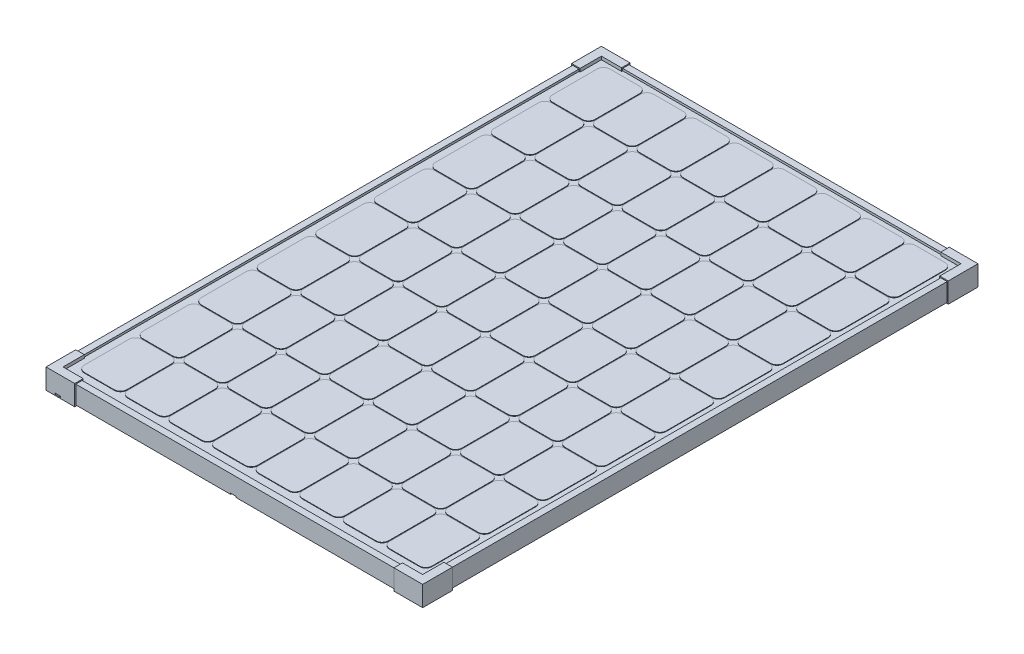
SolidWorks part; units mm, degrees
material "Aleación 1060"
ref_plane "Plan de face" through (0, 0, 0) normal (0, 0, 1) x (1, 0, 0)
ref_plane "Plan de dessus" through (0, 0, 0) normal (0, 1, 0) x (1, 0, 0)
ref_plane "Plan de droite" through (0, 0, 0) normal (1, 0, 0) x (0, 0, -1)
sketch "Croquis1" plane through (0, 0, 0) normal (0, 1, 0) x (1, 0, 0)
  line L1 (0, 0) -> (352, 0)
  line L2 (0, 0) -> (0, 520)
  line L3 (0, 520) -> (352, 520)
  line L4 (352, 0) -> (352, 520)
  dimension "D1" = 520
  dimension "D2" = 352
extrude "Saliente-Extruir1" add sketch "Croquis1" along normal blind 17
sketch "Croquis3" plane through (0, 17, 0) normal (0, 1, 0) x (1, 0, 0)
  line L0 (346, 6) -> (346, 514)
  line L1 (346, 514) -> (6, 514)
  line L2 (6, 514) -> (6, 6)
  line L3 (6, 6) -> (346, 6)
  line L5 (352, 520) -> (0, 520) construction
  line L6 (0, 0) -> (352, 0) construction
  line L7 (0, 520) -> (0, 0) construction
  line L8 (352, 0) -> (352, 520) construction
  dimension "D1" = 6
  dimension "D2" = 6
  dimension "D3" = 6
  dimension "D4" = 6
extrude "Cortar-Extruir1" cut sketch "Croquis3" against normal blind 2
shell "Vaciado1" thickness 1
sketch "Croquis2" plane through (0, 0, 0) normal (0, -1, 0) x (1, 0, 0)
  line L0 (17, -17) -> (17, -503)
  line L1 (17, -503) -> (335, -503)
  line L2 (335, -503) -> (335, -17)
  line L3 (335, -17) -> (17, -17)
  line L4 (0, 0) -> (0, -520)
  line L5 (0, -520) -> (352, -520)
  line L6 (352, -520) -> (352, 0)
  line L7 (352, 0) -> (0, 0)
  line L8 (0, 0) -> (0, -520)
  line L9 (0, -520) -> (352, -520)
  line L10 (352, -520) -> (352, 0)
  line L11 (352, 0) -> (0, 0)
  dimension "D1" = 0
  dimension "D2" = 17
extrude "Saliente-Extruir2" add sketch "Croquis2" against normal blind 1
sketch "Croquis4" plane through (0, 17, 0) normal (0, 1, 0) x (1, 0, 0)
  line L1 (0, 520) -> (0, 0) construction
  line L2 (6, 514) -> (6, 6) construction
  line L3 (352, 520) -> (0, 520) construction
  line L4 (346, 514) -> (6, 514) construction
  line L8 (26, 521) -> (-1, 521)
  line L9 (-1, 521) -> (-1, 493)
  line L10 (26, 513) -> (7, 513)
  line L11 (7, 513) -> (7, 493)
  line L12 (26, 521) -> (26, 513)
  line L13 (-1, 493) -> (7, 493)
  point P16 (3, 493)
  dimension "D3" = 27
  dimension "D4" = 28
  dimension "D1" = 1
  dimension "D2" = 1
  dimension "D5" = 1
  dimension "D6" = 1
extrude "Saliente-Extruir3" add sketch "Croquis4" along normal blind 1 and the other way blind 17
sketch "Croquis5" plane through (0, 0, 0) normal (0, -1, 0) x (1, 0, 0)
  line L2 (-1, -521) -> (-1, -493)
  line L3 (26, -521) -> (-1, -521)
  line L4 (-1, -493) -> (18, -493)
  line L5 (18, -493) -> (18, -502)
  line L6 (18, -502) -> (26, -502)
  line L7 (26, -502) -> (26, -521)
  line L9 (17, -17) -> (17, -503) construction
  line L10 (0, -493) -> (0, 0) construction
  dimension "D1" = 19
  dimension "D2" = 9
  dimension "D3" = 27
  dimension "D4" = 1
  dimension "D5" = 1
  dimension "D6" = 19
  dimension "D7" = 8
  dimension "D8" = 28
  dimension "D9" = 521
extrude "Saliente-Extruir4" add sketch "Croquis5" along normal blind 1 and the other way blind 1
ref_plane "Plano1" through (0, 0, -260) normal (0, 0, 1) x (1, 0, 0)
mirror "Simetría1" about plane through (0, 0, -260) normal (0, 0, 1) of "Saliente-Extruir3", "Saliente-Extruir4"
ref_plane "Plano2" through (176, 0, 0) normal (-1, 0, 0) x (0, 0, 1)
mirror "Simetría2" about plane through (176, 0, 0) normal (-1, 0, 0) of "Simetría1", "Saliente-Extruir3", "Saliente-Extruir4"
sketch "Croquis6" plane through (0, 0, 0) normal (0, -1, 0) x (1, 0, 0)
  line L0 (10, -646.4035) -> (10, 241.4035) construction
  line L1 (7.5, -646.4035) -> (7.5, 241.4035)
  line L2 (12.5, -646.4035) -> (12.5, 241.4035)
  line L4 (0, -493) -> (0, -27) construction
  line L5 (17, -27) -> (17, -493) construction
  arc A0 (7.5, -646.4035) -> (12.5, -646.4035) centre (10, -646.4035) ccw
  arc A1 (12.5, 241.4035) -> (7.5, 241.4035) centre (10, 241.4035) ccw
  point P2 (10, -202.5)
  point P11 (17, -260)
  dimension "D1" = 10
  dimension "D2" = 57.5
extrude "Cortar-Extruir2" cut sketch "Croquis6" against normal blind 1
pattern_linear "MatrizL1" count 2 spacing 164 along (1, 0, 0) count 2 spacing 115 along (0, 0, -1) of "Cortar-Extruir2"
sketch "Croquis7" plane through (0, 14, 0) normal (0, -1, 0) x (1, 0, 0)
  line L0 (326, -17) -> (176.5, -17) construction
  line L1 (234.5, -93) -> (284.5, -93)
  line L2 (234.5, -93) -> (234.5, -26)
  line L3 (234.5, -26) -> (284.5, -26)
  line L4 (284.5, -93) -> (284.5, -26)
  line L5 (234.5, -93) -> (284.5, -26) construction
  line L6 (234.5, -26) -> (284.5, -93) construction
  line L7 (352, -27) -> (352, -493) construction
  point P0 (259.5, -59.5)
  dimension "D1" = 67
  dimension "D2" = 50
  dimension "D3" = 9
  dimension "D4" = 92.5
extrude "Saliente-Extruir5" add sketch "Croquis7" along normal blind 14
fillet "Redondeo1" radius 3 4 edges at (284.5, 7, -26) (234.5, 7, -26) (234.5, 7, -93) (284.5, 7, -93)
sketch "Croquis8" plane through (0, 15, 0) normal (0, 1, 0) x (1, 0, 0)
  line L0 (326, 514) -> (26, 514) construction
  line L1 (19, 509) -> (47, 509)
  line L2 (13, 503) -> (13, 461)
  line L3 (19, 455) -> (47, 455)
  line L4 (53, 503) -> (53, 461)
  line L5 (6, 493) -> (6, 27) construction
  line L6 (60, 509) -> (88, 509)
  line L7 (54, 503) -> (54, 461)
  line L8 (60, 455) -> (88, 455)
  line L9 (94, 503) -> (94, 461)
  line L10 (101, 509) -> (129, 509)
  line L11 (95, 503) -> (95, 461)
  line L12 (101, 455) -> (129, 455)
  line L13 (135, 503) -> (135, 461)
  line L14 (142, 509) -> (170, 509)
  line L15 (136, 503) -> (136, 461)
  line L16 (142, 455) -> (170, 455)
  line L17 (176, 503) -> (176, 461)
  line L18 (183, 509) -> (211, 509)
  line L19 (177, 503) -> (177, 461)
  line L20 (183, 455) -> (211, 455)
  line L21 (217, 503) -> (217, 461)
  line L22 (224, 509) -> (252, 509)
  line L23 (218, 503) -> (218, 461)
  line L24 (224, 455) -> (252, 455)
  line L25 (258, 503) -> (258, 461)
  line L26 (265, 509) -> (293, 509)
  line L27 (259, 503) -> (259, 461)
  line L28 (265, 455) -> (293, 455)
  line L29 (299, 503) -> (299, 461)
  line L30 (306, 509) -> (334, 509)
  line L31 (300, 503) -> (300, 461)
  line L32 (306, 455) -> (334, 455)
  line L33 (340, 503) -> (340, 461)
  line L34 (60, 454) -> (88, 454)
  line L35 (54, 448) -> (54, 406)
  line L36 (60, 400) -> (88, 400)
  line L37 (94, 448) -> (94, 406)
  line L38 (101, 454) -> (129, 454)
  line L39 (95, 448) -> (95, 406)
  line L40 (101, 400) -> (129, 400)
  line L41 (135, 448) -> (135, 406)
  line L42 (142, 454) -> (170, 454)
  line L43 (136, 448) -> (136, 406)
  line L44 (142, 400) -> (170, 400)
  line L45 (176, 448) -> (176, 406)
  line L46 (183, 454) -> (211, 454)
  line L47 (177, 448) -> (177, 406)
  line L48 (183, 400) -> (211, 400)
  line L49 (217, 448) -> (217, 406)
  line L50 (224, 454) -> (252, 454)
  line L51 (218, 448) -> (218, 406)
  line L52 (224, 400) -> (252, 400)
  line L53 (258, 448) -> (258, 406)
  line L54 (265, 454) -> (293, 454)
  line L55 (259, 448) -> (259, 406)
  line L56 (265, 400) -> (293, 400)
  line L57 (299, 448) -> (299, 406)
  line L58 (306, 454) -> (334, 454)
  line L59 (300, 448) -> (300, 406)
  line L60 (306, 400) -> (334, 400)
  line L61 (340, 448) -> (340, 406)
  line L62 (60, 399) -> (88, 399)
  line L63 (54, 393) -> (54, 351)
  line L64 (60, 345) -> (88, 345)
  line L65 (94, 393) -> (94, 351)
  line L66 (101, 399) -> (129, 399)
  line L67 (95, 393) -> (95, 351)
  line L68 (101, 345) -> (129, 345)
  line L69 (135, 393) -> (135, 351)
  line L70 (142, 399) -> (170, 399)
  line L71 (136, 393) -> (136, 351)
  line L72 (142, 345) -> (170, 345)
  line L73 (176, 393) -> (176, 351)
  line L74 (183, 399) -> (211, 399)
  line L75 (177, 393) -> (177, 351)
  line L76 (183, 345) -> (211, 345)
  line L77 (217, 393) -> (217, 351)
  line L78 (224, 399) -> (252, 399)
  line L79 (218, 393) -> (218, 351)
  line L80 (224, 345) -> (252, 345)
  line L81 (258, 393) -> (258, 351)
  line L82 (265, 399) -> (293, 399)
  line L83 (259, 393) -> (259, 351)
  line L84 (265, 345) -> (293, 345)
  line L85 (299, 393) -> (299, 351)
  line L86 (306, 399) -> (334, 399)
  line L87 (300, 393) -> (300, 351)
  line L88 (306, 345) -> (334, 345)
  line L89 (340, 393) -> (340, 351)
  line L90 (60, 344) -> (88, 344)
  line L91 (54, 338) -> (54, 296)
  line L92 (60, 290) -> (88, 290)
  line L93 (94, 338) -> (94, 296)
  line L94 (101, 344) -> (129, 344)
  line L95 (95, 338) -> (95, 296)
  line L96 (101, 290) -> (129, 290)
  line L97 (135, 338) -> (135, 296)
  line L98 (142, 344) -> (170, 344)
  line L99 (136, 338) -> (136, 296)
  line L100 (142, 290) -> (170, 290)
  line L101 (176, 338) -> (176, 296)
  line L102 (183, 344) -> (211, 344)
  line L103 (177, 338) -> (177, 296)
  line L104 (183, 290) -> (211, 290)
  line L105 (217, 338) -> (217, 296)
  line L106 (224, 344) -> (252, 344)
  line L107 (218, 338) -> (218, 296)
  line L108 (224, 290) -> (252, 290)
  line L109 (258, 338) -> (258, 296)
  line L110 (265, 344) -> (293, 344)
  line L111 (259, 338) -> (259, 296)
  line L112 (265, 290) -> (293, 290)
  line L113 (299, 338) -> (299, 296)
  line L114 (306, 344) -> (334, 344)
  line L115 (300, 338) -> (300, 296)
  line L116 (306, 290) -> (334, 290)
  line L117 (340, 338) -> (340, 296)
  line L118 (60, 289) -> (88, 289)
  line L119 (54, 283) -> (54, 241)
  line L120 (60, 235) -> (88, 235)
  line L121 (94, 283) -> (94, 241)
  line L122 (101, 289) -> (129, 289)
  line L123 (95, 283) -> (95, 241)
  line L124 (101, 235) -> (129, 235)
  line L125 (135, 283) -> (135, 241)
  line L126 (142, 289) -> (170, 289)
  line L127 (136, 283) -> (136, 241)
  line L128 (142, 235) -> (170, 235)
  line L129 (176, 283) -> (176, 241)
  line L130 (183, 289) -> (211, 289)
  line L131 (177, 283) -> (177, 241)
  line L132 (183, 235) -> (211, 235)
  line L133 (217, 283) -> (217, 241)
  line L134 (224, 289) -> (252, 289)
  line L135 (218, 283) -> (218, 241)
  line L136 (224, 235) -> (252, 235)
  line L137 (258, 283) -> (258, 241)
  line L138 (265, 289) -> (293, 289)
  line L139 (259, 283) -> (259, 241)
  line L140 (265, 235) -> (293, 235)
  line L141 (299, 283) -> (299, 241)
  line L142 (306, 289) -> (334, 289)
  line L143 (300, 283) -> (300, 241)
  line L144 (306, 235) -> (334, 235)
  line L145 (340, 283) -> (340, 241)
  line L146 (60, 234) -> (88, 234)
  line L147 (54, 228) -> (54, 186)
  line L148 (60, 180) -> (88, 180)
  line L149 (94, 228) -> (94, 186)
  line L150 (101, 234) -> (129, 234)
  line L151 (95, 228) -> (95, 186)
  line L152 (101, 180) -> (129, 180)
  line L153 (135, 228) -> (135, 186)
  line L154 (142, 234) -> (170, 234)
  line L155 (136, 228) -> (136, 186)
  line L156 (142, 180) -> (170, 180)
  line L157 (176, 228) -> (176, 186)
  line L158 (183, 234) -> (211, 234)
  line L159 (177, 228) -> (177, 186)
  line L160 (183, 180) -> (211, 180)
  line L161 (217, 228) -> (217, 186)
  line L162 (224, 234) -> (252, 234)
  line L163 (218, 228) -> (218, 186)
  line L164 (224, 180) -> (252, 180)
  line L165 (258, 228) -> (258, 186)
  line L166 (265, 234) -> (293, 234)
  line L167 (259, 228) -> (259, 186)
  line L168 (265, 180) -> (293, 180)
  line L169 (299, 228) -> (299, 186)
  line L170 (306, 234) -> (334, 234)
  line L171 (300, 228) -> (300, 186)
  line L172 (306, 180) -> (334, 180)
  line L173 (340, 228) -> (340, 186)
  line L174 (60, 179) -> (88, 179)
  line L175 (54, 173) -> (54, 131)
  line L176 (60, 125) -> (88, 125)
  line L177 (94, 173) -> (94, 131)
  line L178 (101, 179) -> (129, 179)
  line L179 (95, 173) -> (95, 131)
  line L180 (101, 125) -> (129, 125)
  line L181 (135, 173) -> (135, 131)
  line L182 (142, 179) -> (170, 179)
  line L183 (136, 173) -> (136, 131)
  line L184 (142, 125) -> (170, 125)
  line L185 (176, 173) -> (176, 131)
  line L186 (183, 179) -> (211, 179)
  line L187 (177, 173) -> (177, 131)
  line L188 (183, 125) -> (211, 125)
  line L189 (217, 173) -> (217, 131)
  line L190 (224, 179) -> (252, 179)
  line L191 (218, 173) -> (218, 131)
  line L192 (224, 125) -> (252, 125)
  line L193 (258, 173) -> (258, 131)
  line L194 (265, 179) -> (293, 179)
  line L195 (259, 173) -> (259, 131)
  line L196 (265, 125) -> (293, 125)
  line L197 (299, 173) -> (299, 131)
  line L198 (306, 179) -> (334, 179)
  line L199 (300, 173) -> (300, 131)
  line L200 (306, 125) -> (334, 125)
  line L201 (340, 173) -> (340, 131)
  line L202 (60, 124) -> (88, 124)
  line L203 (54, 118) -> (54, 76)
  line L204 (60, 70) -> (88, 70)
  line L205 (94, 118) -> (94, 76)
  line L206 (101, 124) -> (129, 124)
  line L207 (95, 118) -> (95, 76)
  line L208 (101, 70) -> (129, 70)
  line L209 (135, 118) -> (135, 76)
  line L210 (142, 124) -> (170, 124)
  line L211 (136, 118) -> (136, 76)
  line L212 (142, 70) -> (170, 70)
  line L213 (176, 118) -> (176, 76)
  line L214 (183, 124) -> (211, 124)
  line L215 (177, 118) -> (177, 76)
  line L216 (183, 70) -> (211, 70)
  line L217 (217, 118) -> (217, 76)
  line L218 (224, 124) -> (252, 124)
  line L219 (218, 118) -> (218, 76)
  line L220 (224, 70) -> (252, 70)
  line L221 (258, 118) -> (258, 76)
  line L222 (265, 124) -> (293, 124)
  line L223 (259, 118) -> (259, 76)
  line L224 (265, 70) -> (293, 70)
  line L225 (299, 118) -> (299, 76)
  line L226 (306, 124) -> (334, 124)
  line L227 (300, 118) -> (300, 76)
  line L228 (306, 70) -> (334, 70)
  line L229 (340, 118) -> (340, 76)
  line L230 (60, 69) -> (88, 69)
  line L231 (54, 63) -> (54, 21)
  line L232 (60, 15) -> (88, 15)
  line L233 (94, 63) -> (94, 21)
  line L234 (101, 69) -> (129, 69)
  line L235 (95, 63) -> (95, 21)
  line L236 (101, 15) -> (129, 15)
  line L237 (135, 63) -> (135, 21)
  line L238 (142, 69) -> (170, 69)
  line L239 (136, 63) -> (136, 21)
  line L240 (142, 15) -> (170, 15)
  line L241 (176, 63) -> (176, 21)
  line L242 (183, 69) -> (211, 69)
  line L243 (177, 63) -> (177, 21)
  line L244 (183, 15) -> (211, 15)
  line L245 (217, 63) -> (217, 21)
  line L246 (224, 69) -> (252, 69)
  line L247 (218, 63) -> (218, 21)
  line L248 (224, 15) -> (252, 15)
  line L249 (258, 63) -> (258, 21)
  line L250 (265, 69) -> (293, 69)
  line L251 (259, 63) -> (259, 21)
  line L252 (265, 15) -> (293, 15)
  line L253 (299, 63) -> (299, 21)
  line L254 (306, 69) -> (334, 69)
  line L255 (300, 63) -> (300, 21)
  line L256 (306, 15) -> (334, 15)
  line L257 (340, 63) -> (340, 21)
  line L258 (19, 454) -> (47, 454)
  line L259 (13, 448) -> (13, 406)
  line L260 (19, 400) -> (47, 400)
  line L261 (53, 448) -> (53, 406)
  line L262 (19, 399) -> (47, 399)
  line L263 (13, 393) -> (13, 351)
  line L264 (19, 345) -> (47, 345)
  line L265 (53, 393) -> (53, 351)
  line L266 (19, 344) -> (47, 344)
  line L267 (13, 338) -> (13, 296)
  line L268 (19, 290) -> (47, 290)
  line L269 (53, 338) -> (53, 296)
  line L270 (19, 289) -> (47, 289)
  line L271 (13, 283) -> (13, 241)
  line L272 (19, 235) -> (47, 235)
  line L273 (53, 283) -> (53, 241)
  line L274 (19, 234) -> (47, 234)
  line L275 (13, 228) -> (13, 186)
  line L276 (19, 180) -> (47, 180)
  line L277 (53, 228) -> (53, 186)
  line L278 (19, 179) -> (47, 179)
  line L279 (13, 173) -> (13, 131)
  line L280 (19, 125) -> (47, 125)
  line L281 (53, 173) -> (53, 131)
  line L282 (19, 124) -> (47, 124)
  line L283 (13, 118) -> (13, 76)
  line L284 (19, 70) -> (47, 70)
  line L285 (53, 118) -> (53, 76)
  line L286 (19, 69) -> (47, 69)
  line L287 (13, 63) -> (13, 21)
  line L288 (19, 15) -> (47, 15)
  line L289 (53, 63) -> (53, 21)
  line L291 (326, 514) -> (26, 514) construction
  arc A0 (19, 509) -> (13, 503) centre (19, 503) ccw
  arc A1 (13, 461) -> (19, 455) centre (19, 461) ccw
  arc A2 (53, 461) -> (47, 455) centre (47, 461) cw
  arc A3 (53, 503) -> (47, 509) centre (47, 503) ccw
  arc A4 (60, 509) -> (54, 503) centre (60, 503) ccw
  arc A5 (54, 461) -> (60, 455) centre (60, 461) ccw
  arc A6 (94, 461) -> (88, 455) centre (88, 461) cw
  arc A7 (94, 503) -> (88, 509) centre (88, 503) ccw
  arc A8 (101, 509) -> (95, 503) centre (101, 503) ccw
  arc A9 (95, 461) -> (101, 455) centre (101, 461) ccw
  arc A10 (135, 461) -> (129, 455) centre (129, 461) cw
  arc A11 (135, 503) -> (129, 509) centre (129, 503) ccw
  arc A12 (142, 509) -> (136, 503) centre (142, 503) ccw
  arc A13 (136, 461) -> (142, 455) centre (142, 461) ccw
  arc A14 (176, 461) -> (170, 455) centre (170, 461) cw
  arc A15 (176, 503) -> (170, 509) centre (170, 503) ccw
  arc A16 (183, 509) -> (177, 503) centre (183, 503) ccw
  arc A17 (177, 461) -> (183, 455) centre (183, 461) ccw
  arc A18 (217, 461) -> (211, 455) centre (211, 461) cw
  arc A19 (217, 503) -> (211, 509) centre (211, 503) ccw
  arc A20 (224, 509) -> (218, 503) centre (224, 503) ccw
  arc A21 (218, 461) -> (224, 455) centre (224, 461) ccw
  arc A22 (258, 461) -> (252, 455) centre (252, 461) cw
  arc A23 (258, 503) -> (252, 509) centre (252, 503) ccw
  arc A24 (265, 509) -> (259, 503) centre (265, 503) ccw
  arc A25 (259, 461) -> (265, 455) centre (265, 461) ccw
  arc A26 (299, 461) -> (293, 455) centre (293, 461) cw
  arc A27 (299, 503) -> (293, 509) centre (293, 503) ccw
  arc A28 (306, 509) -> (300, 503) centre (306, 503) ccw
  arc A29 (300, 461) -> (306, 455) centre (306, 461) ccw
  arc A30 (340, 461) -> (334, 455) centre (334, 461) cw
  arc A31 (340, 503) -> (334, 509) centre (334, 503) ccw
  arc A32 (60, 454) -> (54, 448) centre (60, 448) ccw
  arc A33 (54, 406) -> (60, 400) centre (60, 406) ccw
  arc A34 (94, 406) -> (88, 400) centre (88, 406) cw
  arc A35 (94, 448) -> (88, 454) centre (88, 448) ccw
  arc A36 (101, 454) -> (95, 448) centre (101, 448) ccw
  arc A37 (95, 406) -> (101, 400) centre (101, 406) ccw
  arc A38 (135, 406) -> (129, 400) centre (129, 406) cw
  arc A39 (135, 448) -> (129, 454) centre (129, 448) ccw
  arc A40 (142, 454) -> (136, 448) centre (142, 448) ccw
  arc A41 (136, 406) -> (142, 400) centre (142, 406) ccw
  arc A42 (176, 406) -> (170, 400) centre (170, 406) cw
  arc A43 (176, 448) -> (170, 454) centre (170, 448) ccw
  arc A44 (183, 454) -> (177, 448) centre (183, 448) ccw
  arc A45 (177, 406) -> (183, 400) centre (183, 406) ccw
  arc A46 (217, 406) -> (211, 400) centre (211, 406) cw
  arc A47 (217, 448) -> (211, 454) centre (211, 448) ccw
  arc A48 (224, 454) -> (218, 448) centre (224, 448) ccw
  arc A49 (218, 406) -> (224, 400) centre (224, 406) ccw
  arc A50 (258, 406) -> (252, 400) centre (252, 406) cw
  arc A51 (258, 448) -> (252, 454) centre (252, 448) ccw
  arc A52 (265, 454) -> (259, 448) centre (265, 448) ccw
  arc A53 (259, 406) -> (265, 400) centre (265, 406) ccw
  arc A54 (299, 406) -> (293, 400) centre (293, 406) cw
  arc A55 (299, 448) -> (293, 454) centre (293, 448) ccw
  arc A56 (306, 454) -> (300, 448) centre (306, 448) ccw
  arc A57 (300, 406) -> (306, 400) centre (306, 406) ccw
  arc A58 (340, 406) -> (334, 400) centre (334, 406) cw
  arc A59 (340, 448) -> (334, 454) centre (334, 448) ccw
  arc A60 (60, 399) -> (54, 393) centre (60, 393) ccw
  arc A61 (54, 351) -> (60, 345) centre (60, 351) ccw
  arc A62 (94, 351) -> (88, 345) centre (88, 351) cw
  arc A63 (94, 393) -> (88, 399) centre (88, 393) ccw
  arc A64 (101, 399) -> (95, 393) centre (101, 393) ccw
  arc A65 (95, 351) -> (101, 345) centre (101, 351) ccw
  arc A66 (135, 351) -> (129, 345) centre (129, 351) cw
  arc A67 (135, 393) -> (129, 399) centre (129, 393) ccw
  arc A68 (142, 399) -> (136, 393) centre (142, 393) ccw
  arc A69 (136, 351) -> (142, 345) centre (142, 351) ccw
  arc A70 (176, 351) -> (170, 345) centre (170, 351) cw
  arc A71 (176, 393) -> (170, 399) centre (170, 393) ccw
  arc A72 (183, 399) -> (177, 393) centre (183, 393) ccw
  arc A73 (177, 351) -> (183, 345) centre (183, 351) ccw
  arc A74 (217, 351) -> (211, 345) centre (211, 351) cw
  arc A75 (217, 393) -> (211, 399) centre (211, 393) ccw
  arc A76 (224, 399) -> (218, 393) centre (224, 393) ccw
  arc A77 (218, 351) -> (224, 345) centre (224, 351) ccw
  arc A78 (258, 351) -> (252, 345) centre (252, 351) cw
  arc A79 (258, 393) -> (252, 399) centre (252, 393) ccw
  arc A80 (265, 399) -> (259, 393) centre (265, 393) ccw
  arc A81 (259, 351) -> (265, 345) centre (265, 351) ccw
  arc A82 (299, 351) -> (293, 345) centre (293, 351) cw
  arc A83 (299, 393) -> (293, 399) centre (293, 393) ccw
  arc A84 (306, 399) -> (300, 393) centre (306, 393) ccw
  arc A85 (300, 351) -> (306, 345) centre (306, 351) ccw
  arc A86 (340, 351) -> (334, 345) centre (334, 351) cw
  arc A87 (340, 393) -> (334, 399) centre (334, 393) ccw
  arc A88 (60, 344) -> (54, 338) centre (60, 338) ccw
  arc A89 (54, 296) -> (60, 290) centre (60, 296) ccw
  arc A90 (94, 296) -> (88, 290) centre (88, 296) cw
  arc A91 (94, 338) -> (88, 344) centre (88, 338) ccw
  arc A92 (101, 344) -> (95, 338) centre (101, 338) ccw
  arc A93 (95, 296) -> (101, 290) centre (101, 296) ccw
  arc A94 (135, 296) -> (129, 290) centre (129, 296) cw
  arc A95 (135, 338) -> (129, 344) centre (129, 338) ccw
  arc A96 (142, 344) -> (136, 338) centre (142, 338) ccw
  arc A97 (136, 296) -> (142, 290) centre (142, 296) ccw
  arc A98 (176, 296) -> (170, 290) centre (170, 296) cw
  arc A99 (176, 338) -> (170, 344) centre (170, 338) ccw
  arc A100 (183, 344) -> (177, 338) centre (183, 338) ccw
  arc A101 (177, 296) -> (183, 290) centre (183, 296) ccw
  arc A102 (217, 296) -> (211, 290) centre (211, 296) cw
  arc A103 (217, 338) -> (211, 344) centre (211, 338) ccw
  arc A104 (224, 344) -> (218, 338) centre (224, 338) ccw
  arc A105 (218, 296) -> (224, 290) centre (224, 296) ccw
  arc A106 (258, 296) -> (252, 290) centre (252, 296) cw
  arc A107 (258, 338) -> (252, 344) centre (252, 338) ccw
  arc A108 (265, 344) -> (259, 338) centre (265, 338) ccw
  arc A109 (259, 296) -> (265, 290) centre (265, 296) ccw
  arc A110 (299, 296) -> (293, 290) centre (293, 296) cw
  arc A111 (299, 338) -> (293, 344) centre (293, 338) ccw
  arc A112 (306, 344) -> (300, 338) centre (306, 338) ccw
  arc A113 (300, 296) -> (306, 290) centre (306, 296) ccw
  arc A114 (340, 296) -> (334, 290) centre (334, 296) cw
  arc A115 (340, 338) -> (334, 344) centre (334, 338) ccw
  arc A116 (60, 289) -> (54, 283) centre (60, 283) ccw
  arc A117 (54, 241) -> (60, 235) centre (60, 241) ccw
  arc A118 (94, 241) -> (88, 235) centre (88, 241) cw
  arc A119 (94, 283) -> (88, 289) centre (88, 283) ccw
  arc A120 (101, 289) -> (95, 283) centre (101, 283) ccw
  arc A121 (95, 241) -> (101, 235) centre (101, 241) ccw
  arc A122 (135, 241) -> (129, 235) centre (129, 241) cw
  arc A123 (135, 283) -> (129, 289) centre (129, 283) ccw
  arc A124 (142, 289) -> (136, 283) centre (142, 283) ccw
  arc A125 (136, 241) -> (142, 235) centre (142, 241) ccw
  arc A126 (176, 241) -> (170, 235) centre (170, 241) cw
  arc A127 (176, 283) -> (170, 289) centre (170, 283) ccw
  arc A128 (183, 289) -> (177, 283) centre (183, 283) ccw
  arc A129 (177, 241) -> (183, 235) centre (183, 241) ccw
  arc A130 (217, 241) -> (211, 235) centre (211, 241) cw
  arc A131 (217, 283) -> (211, 289) centre (211, 283) ccw
  arc A132 (224, 289) -> (218, 283) centre (224, 283) ccw
  arc A133 (218, 241) -> (224, 235) centre (224, 241) ccw
  arc A134 (258, 241) -> (252, 235) centre (252, 241) cw
  arc A135 (258, 283) -> (252, 289) centre (252, 283) ccw
  arc A136 (265, 289) -> (259, 283) centre (265, 283) ccw
  arc A137 (259, 241) -> (265, 235) centre (265, 241) ccw
  arc A138 (299, 241) -> (293, 235) centre (293, 241) cw
  arc A139 (299, 283) -> (293, 289) centre (293, 283) ccw
  arc A140 (306, 289) -> (300, 283) centre (306, 283) ccw
  arc A141 (300, 241) -> (306, 235) centre (306, 241) ccw
  arc A142 (340, 241) -> (334, 235) centre (334, 241) cw
  arc A143 (340, 283) -> (334, 289) centre (334, 283) ccw
  arc A144 (60, 234) -> (54, 228) centre (60, 228) ccw
  arc A145 (54, 186) -> (60, 180) centre (60, 186) ccw
  arc A146 (94, 186) -> (88, 180) centre (88, 186) cw
  arc A147 (94, 228) -> (88, 234) centre (88, 228) ccw
  arc A148 (101, 234) -> (95, 228) centre (101, 228) ccw
  arc A149 (95, 186) -> (101, 180) centre (101, 186) ccw
  arc A150 (135, 186) -> (129, 180) centre (129, 186) cw
  arc A151 (135, 228) -> (129, 234) centre (129, 228) ccw
  arc A152 (142, 234) -> (136, 228) centre (142, 228) ccw
  arc A153 (136, 186) -> (142, 180) centre (142, 186) ccw
  arc A154 (176, 186) -> (170, 180) centre (170, 186) cw
  arc A155 (176, 228) -> (170, 234) centre (170, 228) ccw
  arc A156 (183, 234) -> (177, 228) centre (183, 228) ccw
  arc A157 (177, 186) -> (183, 180) centre (183, 186) ccw
  arc A158 (217, 186) -> (211, 180) centre (211, 186) cw
  arc A159 (217, 228) -> (211, 234) centre (211, 228) ccw
  arc A160 (224, 234) -> (218, 228) centre (224, 228) ccw
  arc A161 (218, 186) -> (224, 180) centre (224, 186) ccw
  arc A162 (258, 186) -> (252, 180) centre (252, 186) cw
  arc A163 (258, 228) -> (252, 234) centre (252, 228) ccw
  arc A164 (265, 234) -> (259, 228) centre (265, 228) ccw
  arc A165 (259, 186) -> (265, 180) centre (265, 186) ccw
  arc A166 (299, 186) -> (293, 180) centre (293, 186) cw
  arc A167 (299, 228) -> (293, 234) centre (293, 228) ccw
  arc A168 (306, 234) -> (300, 228) centre (306, 228) ccw
  arc A169 (300, 186) -> (306, 180) centre (306, 186) ccw
  arc A170 (340, 186) -> (334, 180) centre (334, 186) cw
  arc A171 (340, 228) -> (334, 234) centre (334, 228) ccw
  arc A172 (60, 179) -> (54, 173) centre (60, 173) ccw
  arc A173 (54, 131) -> (60, 125) centre (60, 131) ccw
  arc A174 (94, 131) -> (88, 125) centre (88, 131) cw
  arc A175 (94, 173) -> (88, 179) centre (88, 173) ccw
  arc A176 (101, 179) -> (95, 173) centre (101, 173) ccw
  arc A177 (95, 131) -> (101, 125) centre (101, 131) ccw
  arc A178 (135, 131) -> (129, 125) centre (129, 131) cw
  arc A179 (135, 173) -> (129, 179) centre (129, 173) ccw
  arc A180 (142, 179) -> (136, 173) centre (142, 173) ccw
  arc A181 (136, 131) -> (142, 125) centre (142, 131) ccw
  arc A182 (176, 131) -> (170, 125) centre (170, 131) cw
  arc A183 (176, 173) -> (170, 179) centre (170, 173) ccw
  arc A184 (183, 179) -> (177, 173) centre (183, 173) ccw
  arc A185 (177, 131) -> (183, 125) centre (183, 131) ccw
  arc A186 (217, 131) -> (211, 125) centre (211, 131) cw
  arc A187 (217, 173) -> (211, 179) centre (211, 173) ccw
  arc A188 (224, 179) -> (218, 173) centre (224, 173) ccw
  arc A189 (218, 131) -> (224, 125) centre (224, 131) ccw
  arc A190 (258, 131) -> (252, 125) centre (252, 131) cw
  arc A191 (258, 173) -> (252, 179) centre (252, 173) ccw
  arc A192 (265, 179) -> (259, 173) centre (265, 173) ccw
  arc A193 (259, 131) -> (265, 125) centre (265, 131) ccw
  arc A194 (299, 131) -> (293, 125) centre (293, 131) cw
  arc A195 (299, 173) -> (293, 179) centre (293, 173) ccw
  arc A196 (306, 179) -> (300, 173) centre (306, 173) ccw
  arc A197 (300, 131) -> (306, 125) centre (306, 131) ccw
  arc A198 (340, 131) -> (334, 125) centre (334, 131) cw
  arc A199 (340, 173) -> (334, 179) centre (334, 173) ccw
  arc A200 (60, 124) -> (54, 118) centre (60, 118) ccw
  arc A201 (54, 76) -> (60, 70) centre (60, 76) ccw
  arc A202 (94, 76) -> (88, 70) centre (88, 76) cw
  arc A203 (94, 118) -> (88, 124) centre (88, 118) ccw
  arc A204 (101, 124) -> (95, 118) centre (101, 118) ccw
  arc A205 (95, 76) -> (101, 70) centre (101, 76) ccw
  arc A206 (135, 76) -> (129, 70) centre (129, 76) cw
  arc A207 (135, 118) -> (129, 124) centre (129, 118) ccw
  arc A208 (142, 124) -> (136, 118) centre (142, 118) ccw
  arc A209 (136, 76) -> (142, 70) centre (142, 76) ccw
  arc A210 (176, 76) -> (170, 70) centre (170, 76) cw
  arc A211 (176, 118) -> (170, 124) centre (170, 118) ccw
  arc A212 (183, 124) -> (177, 118) centre (183, 118) ccw
  arc A213 (177, 76) -> (183, 70) centre (183, 76) ccw
  arc A214 (217, 76) -> (211, 70) centre (211, 76) cw
  arc A215 (217, 118) -> (211, 124) centre (211, 118) ccw
  arc A216 (224, 124) -> (218, 118) centre (224, 118) ccw
  arc A217 (218, 76) -> (224, 70) centre (224, 76) ccw
  arc A218 (258, 76) -> (252, 70) centre (252, 76) cw
  arc A219 (258, 118) -> (252, 124) centre (252, 118) ccw
  arc A220 (265, 124) -> (259, 118) centre (265, 118) ccw
  arc A221 (259, 76) -> (265, 70) centre (265, 76) ccw
  arc A222 (299, 76) -> (293, 70) centre (293, 76) cw
  arc A223 (299, 118) -> (293, 124) centre (293, 118) ccw
  arc A224 (306, 124) -> (300, 118) centre (306, 118) ccw
  arc A225 (300, 76) -> (306, 70) centre (306, 76) ccw
  arc A226 (340, 76) -> (334, 70) centre (334, 76) cw
  arc A227 (340, 118) -> (334, 124) centre (334, 118) ccw
  arc A228 (60, 69) -> (54, 63) centre (60, 63) ccw
  arc A229 (54, 21) -> (60, 15) centre (60, 21) ccw
  arc A230 (94, 21) -> (88, 15) centre (88, 21) cw
  arc A231 (94, 63) -> (88, 69) centre (88, 63) ccw
  arc A232 (101, 69) -> (95, 63) centre (101, 63) ccw
  arc A233 (95, 21) -> (101, 15) centre (101, 21) ccw
  arc A234 (135, 21) -> (129, 15) centre (129, 21) cw
  arc A235 (135, 63) -> (129, 69) centre (129, 63) ccw
  arc A236 (142, 69) -> (136, 63) centre (142, 63) ccw
  arc A237 (136, 21) -> (142, 15) centre (142, 21) ccw
  arc A238 (176, 21) -> (170, 15) centre (170, 21) cw
  arc A239 (176, 63) -> (170, 69) centre (170, 63) ccw
  arc A240 (183, 69) -> (177, 63) centre (183, 63) ccw
  arc A241 (177, 21) -> (183, 15) centre (183, 21) ccw
  arc A242 (217, 21) -> (211, 15) centre (211, 21) cw
  arc A243 (217, 63) -> (211, 69) centre (211, 63) ccw
  arc A244 (224, 69) -> (218, 63) centre (224, 63) ccw
  arc A245 (218, 21) -> (224, 15) centre (224, 21) ccw
  arc A246 (258, 21) -> (252, 15) centre (252, 21) cw
  arc A247 (258, 63) -> (252, 69) centre (252, 63) ccw
  arc A248 (265, 69) -> (259, 63) centre (265, 63) ccw
  arc A249 (259, 21) -> (265, 15) centre (265, 21) ccw
  arc A250 (299, 21) -> (293, 15) centre (293, 21) cw
  arc A251 (299, 63) -> (293, 69) centre (293, 63) ccw
  arc A252 (306, 69) -> (300, 63) centre (306, 63) ccw
  arc A253 (300, 21) -> (306, 15) centre (306, 21) ccw
  arc A254 (340, 21) -> (334, 15) centre (334, 21) cw
  arc A255 (340, 63) -> (334, 69) centre (334, 63) ccw
  arc A256 (19, 454) -> (13, 448) centre (19, 448) ccw
  arc A257 (13, 406) -> (19, 400) centre (19, 406) ccw
  arc A258 (53, 406) -> (47, 400) centre (47, 406) cw
  arc A259 (53, 448) -> (47, 454) centre (47, 448) ccw
  arc A260 (19, 399) -> (13, 393) centre (19, 393) ccw
  arc A261 (13, 351) -> (19, 345) centre (19, 351) ccw
  arc A262 (53, 351) -> (47, 345) centre (47, 351) cw
  arc A263 (53, 393) -> (47, 399) centre (47, 393) ccw
  arc A264 (19, 344) -> (13, 338) centre (19, 338) ccw
  arc A265 (13, 296) -> (19, 290) centre (19, 296) ccw
  arc A266 (53, 296) -> (47, 290) centre (47, 296) cw
  arc A267 (53, 338) -> (47, 344) centre (47, 338) ccw
  arc A268 (19, 289) -> (13, 283) centre (19, 283) ccw
  arc A269 (13, 241) -> (19, 235) centre (19, 241) ccw
  arc A270 (53, 241) -> (47, 235) centre (47, 241) cw
  arc A271 (53, 283) -> (47, 289) centre (47, 283) ccw
  arc A272 (19, 234) -> (13, 228) centre (19, 228) ccw
  arc A273 (13, 186) -> (19, 180) centre (19, 186) ccw
  arc A274 (53, 186) -> (47, 180) centre (47, 186) cw
  arc A275 (53, 228) -> (47, 234) centre (47, 228) ccw
  arc A276 (19, 179) -> (13, 173) centre (19, 173) ccw
  arc A277 (13, 131) -> (19, 125) centre (19, 131) ccw
  arc A278 (53, 131) -> (47, 125) centre (47, 131) cw
  arc A279 (53, 173) -> (47, 179) centre (47, 173) ccw
  arc A280 (19, 124) -> (13, 118) centre (19, 118) ccw
  arc A281 (13, 76) -> (19, 70) centre (19, 76) ccw
  arc A282 (53, 76) -> (47, 70) centre (47, 76) cw
  arc A283 (53, 118) -> (47, 124) centre (47, 118) ccw
  arc A284 (19, 69) -> (13, 63) centre (19, 63) ccw
  arc A285 (13, 21) -> (19, 15) centre (19, 21) ccw
  arc A286 (53, 21) -> (47, 15) centre (47, 21) cw
  arc A287 (53, 63) -> (47, 69) centre (47, 63) ccw
  point P10 (13, 509)
  point P15 (53, 455)
  point P18 (53, 509)
  dimension "D5" = 6
  dimension "D1" = 5
  dimension "D2" = 7
  dimension "D3" = 40
  dimension "D4" = 54
  dimension "D8" = 48
  dimension "D9" = 60
  dimension "D10" = 7
  dimension "D6" = 8
  dimension "D7" = 9
extrude "Saliente-Extruir6" add sketch "Croquis8" along normal blind 0.5
